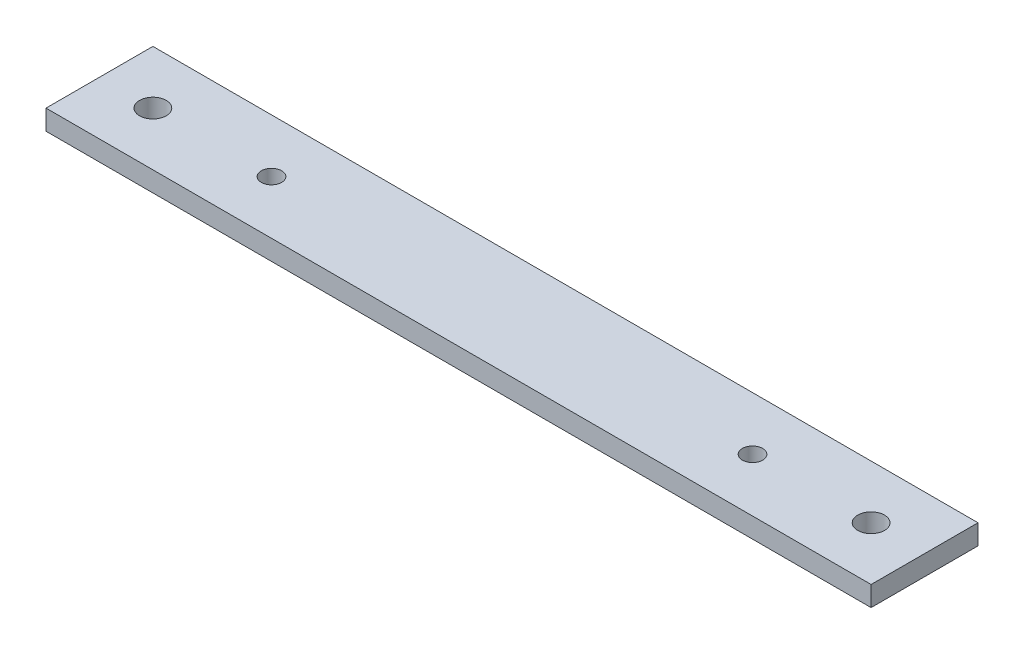
SolidWorks part; units mm, degrees
material "6061-T6 (SS)"
ref_plane "Front Plane" through (0, 0, 0) normal (0, 0, 1) x (1, 0, 0)
ref_plane "Top Plane" through (0, 0, 0) normal (0, 1, 0) x (1, 0, 0)
ref_plane "Right Plane" through (0, 0, 0) normal (1, 0, 0) x (0, 0, -1)
sketch "Sketch1" plane through (0, 0, 0) normal (0, 1, 0) x (1, 0, 0)
  line L1 (98.0313, -12.7) -> (-98.0313, -12.7)
  line L2 (98.0313, -12.7) -> (98.0313, 12.7)
  line L3 (98.0313, 12.7) -> (-98.0313, 12.7)
  line L4 (-98.0313, -12.7) -> (-98.0313, 12.7)
  line L5 (98.0313, -12.7) -> (-98.0313, 12.7) construction
  line L6 (98.0313, 12.7) -> (-98.0313, -12.7) construction
  point P0 (0, 0)
  dimension "D1" = 196.0626
  dimension "D2" = 25.4
extrude "Boss-Extrude1" add sketch "Sketch1" along normal blind 4.7625
sketch "Sketch2" plane through (0, 4.7625, 0) normal (0, 1, 0) x (1, 0, 0)
  line L0 (98.0313, -12.7) -> (98.0313, 12.7) construction
  line L1 (-98.0313, 12.7) -> (-98.0313, -12.7) construction
  circle A0 centre (-57.15, 0) radius 2.413
  circle A1 centre (57.15, 0) radius 2.413
  circle A2 centre (-85.3313, 0) radius 3.175
  circle A3 centre (85.3313, 0) radius 3.175
  dimension "D1" = 4.826
  dimension "D2" = 4.826
  dimension "D5" = 6.35
  dimension "D6" = 6.35
  dimension "D3" = 40.8813
  dimension "D4" = 40.8813
  dimension "D7" = 12.7
  dimension "D8" = 12.7
extrude "Cut-Extrude1" cut sketch "Sketch2" against normal through all
